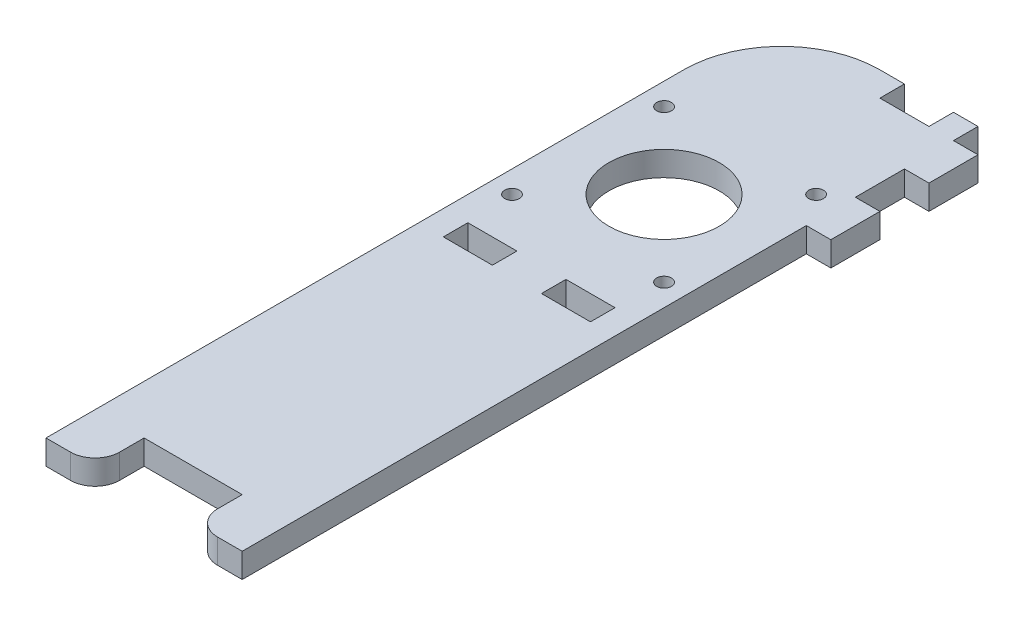
SolidWorks part; units mm, degrees
ref_plane "前视基准面" through (0, 0, 0) normal (0, 0, 1) x (1, 0, 0)
ref_plane "上视基准面" through (0, 0, 0) normal (0, 1, 0) x (1, 0, 0)
ref_plane "右视基准面" through (0, 0, 0) normal (1, 0, 0) x (0, 0, -1)
sketch "草图1" plane through (0, 0, 0) normal (0, 1, 0) x (1, 0, 0)
  line L0 (10, 5) -> (10, 10)
  line L1 (0, 0) -> (5, 0)
  line L2 (0, 0) -> (0, 130)
  line L3 (20, 150) -> (25, 150)
  line L4 (40, 0) -> (40, 115)
  line L5 (10, 10) -> (30, 10)
  line L6 (30, 10) -> (30, 5)
  line L7 (35, 0) -> (40, 0)
  line L8 (-35.4894, 145) -> (63.0619, 145) construction
  line L9 (-37.9463, 138) -> (58.967, 138) construction
  line L10 (-37.9463, 106) -> (65.7919, 106) construction
  line L11 (-37.9463, 81) -> (65.7919, 81) construction
  line L12 (-41.7683, 76) -> (71.7683, 76) construction
  line L13 (20, 162.7582) -> (20, 29.9069) construction
  line L14 (40, 145) -> (40, 150)
  line L15 (25, 150) -> (25, 145)
  line L16 (25, 145) -> (35, 145)
  line L17 (35, 150) -> (35, 145)
  line L18 (5, 81) -> (15, 81)
  line L19 (5, 81) -> (5, 76)
  line L20 (5, 76) -> (15, 76)
  line L21 (15, 81) -> (15, 76)
  line L22 (25, 81) -> (35, 81)
  line L23 (25, 81) -> (25, 76)
  line L24 (25, 76) -> (35, 76)
  line L25 (35, 81) -> (35, 76)
  line L26 (45, 169.5111) -> (45, 60.4889) construction
  line L27 (35, 150) -> (40, 150)
  line L28 (40, 145) -> (45, 145)
  line L29 (40, 125) -> (40, 135)
  line L30 (40, 135) -> (45, 135)
  line L31 (45, 145) -> (45, 135)
  line L32 (40, 125) -> (45, 125)
  line L34 (40, 115) -> (45, 115)
  line L35 (45, 125) -> (45, 115)
  line L36 (4.5, 121.5) -> (35.5, 121.5) construction
  line L37 (4.5, 121.5) -> (4.5, 90.5) construction
  line L38 (4.5, 90.5) -> (35.5, 90.5) construction
  line L39 (35.5, 121.5) -> (35.5, 90.5) construction
  line L40 (4.5, 121.5) -> (35.5, 90.5) construction
  line L41 (4.5, 90.5) -> (35.5, 121.5) construction
  circle A0 centre (20, 106) radius 11.25
  circle A1 centre (4.5, 121.5) radius 1.5
  circle A2 centre (35.5, 121.5) radius 1.5
  circle A3 centre (4.5, 90.5) radius 1.5
  circle A4 centre (35.5, 90.5) radius 1.5
  arc A5 (30, 5) -> (35, 0) centre (35, 5) ccw
  arc A6 (10, 5) -> (5, 0) centre (5, 5) cw
  arc A7 (0, 130) -> (20, 150) centre (20, 130) cw
  point P55 (30, 0)
  point P58 (10, 0)
  point P61 (0, 150)
  dimension "D18" = 20
  dimension "D17" = 5
  dimension "D1" = 150
  dimension "D2" = 40
  dimension "D3" = 10
  dimension "D4" = 10
  dimension "D5" = 10
  dimension "D6" = 20
  dimension "D7" = 7
  dimension "D8" = 32
  dimension "D9" = 25
  dimension "D10" = 5
  dimension "D11" = 10
  dimension "D12" = 10
  dimension "D13" = 5
  dimension "D14" = 5
  dimension "D15" = 5
  dimension "D16" = 10
  dimension "D20" = 5
  dimension "D21" = 5
  dimension "D22" = 10
  dimension "D23" = 10
  dimension "D24" = 10
extrude "凸台-拉伸2" add sketch "草图1" along normal blind 5
